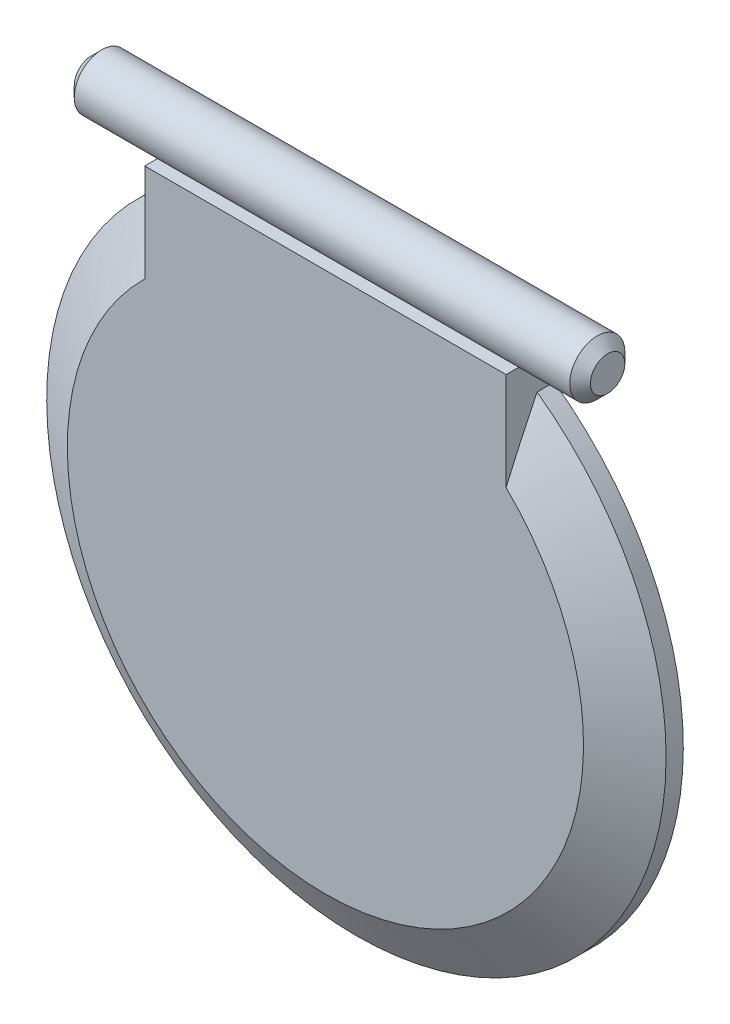
SolidWorks part; units mm, degrees
ref_plane "Front Plane" through (0, 0, 0) normal (0, 0, 1) x (1, 0, 0)
ref_plane "Top Plane" through (0, 0, 0) normal (0, 1, 0) x (1, 0, 0)
ref_plane "Right Plane" through (0, 0, 0) normal (1, 0, 0) x (0, 0, -1)
sketch "Sketch1" plane through (0, 0, 0) normal (0, 0, 1) x (1, 0, 0)
  line L0 (-52.5, 73.101) -> (-52.5, 82)
  line L3 (-52.5, 82) -> (52.5, 82)
  line L5 (52.5, 73.101) -> (52.5, 82)
  line L6 (0, 0) -> (0, 82) construction
  line L7 (75, 0) -> (75, 115.1527) construction
  line L8 (0, 75) -> (33.9069, 75) construction
  arc A0 (-52.5, 73.101) -> (52.5, 73.101) centre (0, 0) ccw
  circle A1 centre (0, 0) radius 75 construction
  dimension "D1" = 15
  dimension "D4" = 150
  dimension "D2" = 14
  dimension "D3" = 105
extrude "Boss-Extrude1" add sketch "Sketch1" along normal mid plane 14
sketch "Sketch2" plane through (0, 0, -7) normal (0, 0, -1) x (-1, 0, 0)
  circle A0 centre (0, 0) radius 90
  dimension "D1" = 180
extrude "Cut-Extrude1" [suppressed] cut sketch "Sketch2" against normal blind 3 draft 10
ref_plane "Plane1" through (0, 0, 4) normal (0, 0, 1) x (1, 0, 0)
sketch "Sketch3" plane through (0, 0, 4) normal (0, 0, 1) x (1, 0, 0)
  circle A0 centre (0, 0) radius 90
  circle A1 centre (0, 0) radius 215.3402
  dimension "D1" = 180
extrude "Cut-Extrude3" [suppressed] cut sketch "Sketch3" along normal blind 33
sketch "Sketch5" [suppressed] plane through (0, 0, 0) normal (1, 0, 0) x (0, 0, -1)
  line L0 (-4, -90) -> (-7, -20)
  line L1 (-7, 90) -> (-7, -90) construction
  line L2 (-7, -20) -> (-7, -90)
  line L3 (-7, -90) -> (-4, -90)
  line L4 (0, 0) -> (-89.3218, 0) construction
  dimension "D1" = 20
revolve "Cut-Revolve1" [suppressed] cut sketch "Sketch5" angle 360 about L4
sketch "Sketch6" plane through (0, 0, 0) normal (1, 0, 0) x (0, 0, -1)
  line L0 (-7, 82) -> (7, 82) construction
  circle A0 centre (0, 90) radius 8
  dimension "D1" = 16
extrude "Boss-Extrude2" add sketch "Sketch6" along normal offset from surface 22.5 and the other way offset from surface (75 mm away) 22.5 separate body up to face at (52.5, 77.5505, 0) offset beyond the face yes other way up to face at (-52.5, 77.5505, 0)
chamfer "Chamfer1" distance 3 angle 45 2 edges at (-75, 90, -8) (75, 90, 8)
sketch "Sketch7" plane through (0, 0, 0) normal (0, 1, 0) x (1, 0, 0)
  line L0 (-90, -7) -> (-90, 2)
  line L1 (-90, 7) -> (-90, -7) construction
  line L2 (-90, 2) -> (-75, -7)
  line L3 (-75, -7) -> (-90, -7)
  line L4 (90, 7) -> (-90, 7) construction
  line L5 (0, 0) -> (0, 43.0511) construction
  dimension "D1" = 15
  dimension "D2" = 5
revolve "Cut-Revolve2" cut sketch "Sketch7" angle 360 about L5
sketch "Sketch11" plane through (0, 0, 7) normal (0, 0, 1) x (1, 0, 0)
  line L0 (52.5, 73.101) -> (52.5, 82) construction
  line L1 (-52.5, 82) -> (52.5, 82)
  line L2 (-52.5, 82) -> (-52.5, 53.5607)
  line L3 (-52.5, 53.5607) -> (52.5, 53.5607)
  line L4 (52.5, 82) -> (52.5, 53.5607)
  circle A0 centre (0, 0) radius 75 construction
extrude "Boss-Extrude3" add sketch "Sketch11" against normal up to surface (14 mm away) up to face at (0, 36.7752, -7)
